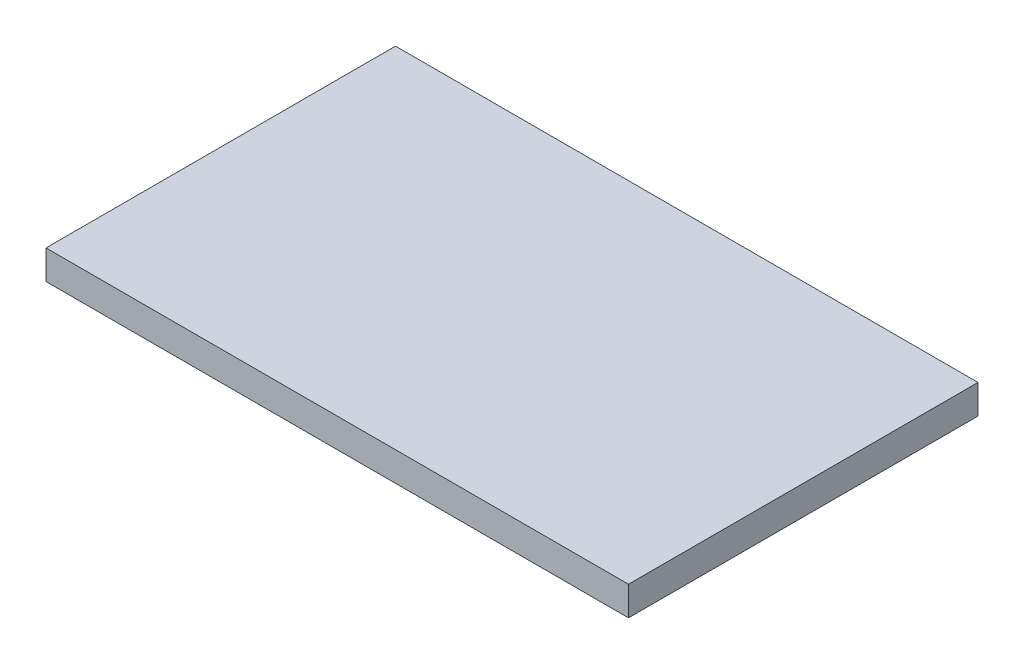
SolidWorks part; units mm, degrees
ref_plane "Front Plane" through (0, 0, 0) normal (0, 0, 1) x (1, 0, 0)
ref_plane "Top Plane" through (0, 0, 0) normal (0, 1, 0) x (1, 0, 0)
ref_plane "Right Plane" through (0, 0, 0) normal (1, 0, 0) x (0, 0, -1)
sketch "Sketch2" plane through (0, 0, 0) normal (0, 1, 0) x (1, 0, 0)
  line L1 (0, 0) -> (200, 0)
  line L2 (0, 0) -> (0, 120)
  line L3 (0, 120) -> (200, 120)
  line L4 (200, 0) -> (200, 120)
  dimension "D1" = 120
  dimension "D2" = 200
extrude "Boss-Extrude1" add sketch "Sketch2" along normal blind 10
